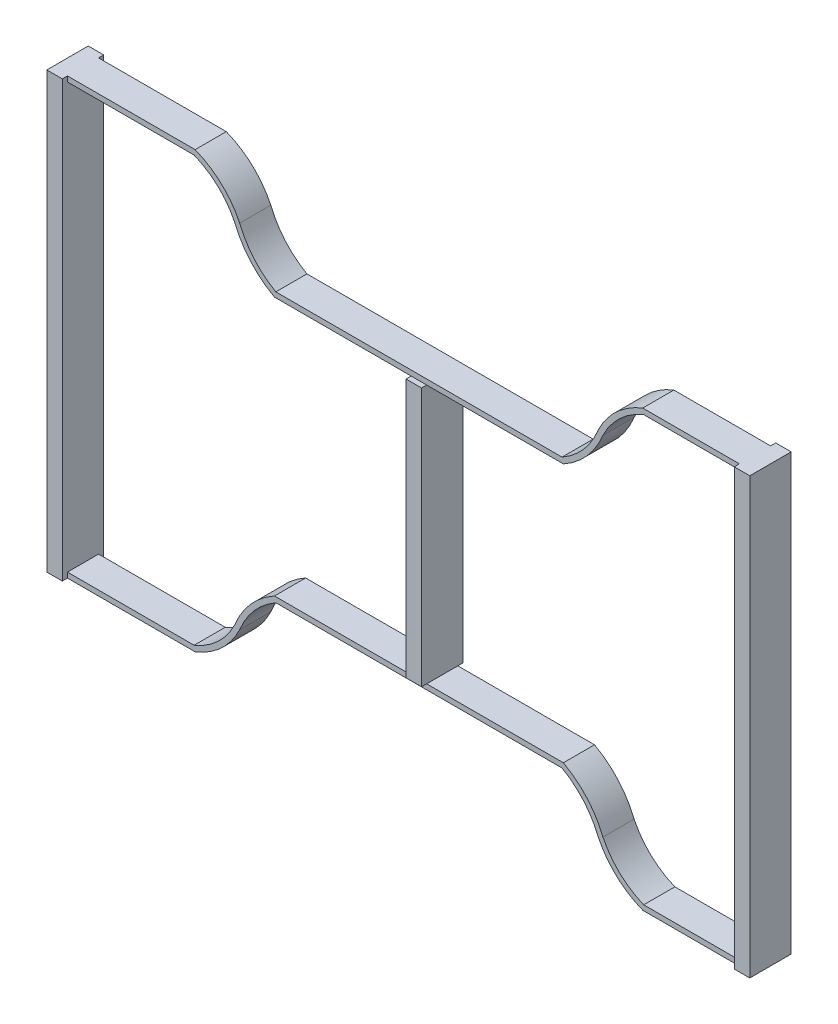
SolidWorks part; units mm, degrees
ref_plane "Front Plane" through (0, 0, 0) normal (0, 0, 1) x (1, 0, 0)
ref_plane "Top Plane" through (0, 0, 0) normal (0, 1, 0) x (1, 0, 0)
ref_plane "Right Plane" through (0, 0, 0) normal (1, 0, 0) x (0, 0, -1)
other "Configuration Table"
sketch "Sketch1" plane through (0, 0, 0) normal (0, 0, 1) x (1, 0, 0)
  line L0 (9.5, 266.7) -> (87.8, 266.7)
  line L1 (0, 0) -> (9.5, 0)
  line L2 (0, 0) -> (0, 266.7)
  line L3 (0, 266.7) -> (9.5, 266.7)
  line L4 (9.5, 0) -> (9.5, 266.7)
  line L5 (137.2756, 215.9) -> (312.7756, 215.9)
  line L6 (362.2513, 266.7) -> (421.5513, 266.7)
  line L7 (9.5, 263.5) -> (87.1857, 263.5)
  line L8 (362.2513, 0) -> (421.5513, 0)
  line L9 (137.2756, 50.8) -> (312.7756, 50.8)
  line L10 (9.5, 0) -> (87.8, 0)
  line L11 (9.5, 0) -> (87.8, 0)
  line L12 (136.4464, 212.7) -> (313.6049, 212.7)
  line L13 (362.8656, 263.5) -> (421.5513, 263.5)
  line L14 (9.5, 266.7) -> (9.5, 263.5)
  line L15 (421.5513, 266.7) -> (421.5513, 263.5)
  line L16 (9.5, 3.2) -> (87.8, 3.2)
  line L17 (136.4464, 54) -> (313.6049, 54)
  line L18 (362.8656, 3.2) -> (421.5513, 3.2)
  line L19 (421.5513, 3.2) -> (421.5513, 0)
  line L20 (9.5, 3.2) -> (9.5, 0)
  line L22 (431.0513, 0) -> (421.5513, 0)
  line L23 (431.0513, 266.7) -> (421.5513, 266.7)
  line L24 (421.5513, 0) -> (421.5513, 266.7)
  line L25 (431.0513, 0) -> (431.0513, 266.7)
  line L26 (229.7756, 212.7) -> (229.7756, 54)
  line L27 (220.2756, 212.7) -> (229.7756, 212.7)
  line L28 (220.2756, 212.7) -> (220.2756, 54)
  line L29 (220.2756, 54) -> (229.7756, 54)
  line L30 (225.0256, 212.7) -> (225.0256, 54)
  arc A0 (87.8, 266.7) -> (115.1137, 241.3) centre (69.2782, 219.3969) cw
  arc A1 (115.1137, 241.3) -> (137.2756, 215.9) centre (162.3044, 260.1063) ccw
  arc A2 (334.9376, 241.3) -> (312.7756, 215.9) centre (287.7469, 260.1063) cw
  arc A3 (362.2513, 266.7) -> (334.9376, 241.3) centre (380.7731, 219.3969) ccw
  arc A4 (362.2513, 0) -> (334.9376, 25.4) centre (380.7731, 47.3031) cw
  arc A5 (334.9376, 25.4) -> (312.7756, 50.8) centre (287.7469, 6.5937) ccw
  arc A6 (87.8, 0) -> (115.1137, 25.4) centre (69.2782, 47.3031) ccw
  arc A7 (115.1137, 25.4) -> (137.2756, 50.8) centre (162.3044, 6.5937) cw
  arc A8 (87.1857, 263.5) -> (112.1818, 240.0133) centre (69.2782, 219.3969) cw
  arc A9 (112.1818, 240.0133) -> (136.4464, 212.7) centre (162.3044, 260.1063) ccw
  arc A10 (337.8694, 240.0133) -> (313.6049, 212.7) centre (287.7469, 260.1063) cw
  arc A11 (362.8656, 263.5) -> (337.8694, 240.0133) centre (380.7731, 219.3969) ccw
  arc A12 (86.6333, 2.9797) -> (112.1818, 26.6867) centre (69.2782, 47.3031) ccw
  arc A13 (112.1818, 26.6867) -> (136.4464, 54) centre (162.3044, 6.5937) cw
  arc A14 (337.8694, 26.6867) -> (313.6049, 54) centre (287.7469, 6.5937) ccw
  arc A15 (362.8656, 3.2) -> (337.8694, 26.6867) centre (380.7731, 47.3031) cw
  dimension "D4" = 25.4
  dimension "D5" = 25.4
  dimension "D1" = 266.7
  dimension "D2" = 9.5
  dimension "D3" = 78.3
  dimension "D6" = 59.3
  dimension "D7" = 3.2
  dimension "D8" = 3.2
  dimension "D9" = 4.75
sketch "Sketch2" plane through (0, 0, 0) normal (0, 0, 1) x (1, 0, 0)
  line L0 (9.5, 266.7) -> (87.8, 266.7)
  line L1 (0, 0) -> (9.5, 0)
  line L2 (0, 0) -> (0, 266.7)
  line L3 (0, 266.7) -> (9.5, 266.7)
  line L4 (9.5, 0) -> (9.5, 266.7)
  line L5 (137.2756, 215.9) -> (312.7756, 215.9)
  line L6 (362.2513, 266.7) -> (421.5513, 266.7)
  line L7 (9.5, 263.5) -> (87.1857, 263.5)
  line L8 (362.2513, 0) -> (421.5513, 0)
  line L9 (137.2756, 50.8) -> (312.7756, 50.8)
  line L10 (9.5, 0) -> (87.8, 0)
  line L11 (9.5, 0) -> (87.8, 0)
  line L12 (136.4464, 212.7) -> (313.6049, 212.7)
  line L13 (362.8656, 263.5) -> (421.5513, 263.5)
  line L14 (9.5, 266.7) -> (9.5, 263.5)
  line L15 (421.5513, 266.7) -> (421.5513, 263.5)
  line L16 (9.5, 3.2) -> (87.8, 3.2)
  line L17 (136.4464, 54) -> (313.6049, 54)
  line L18 (362.8656, 3.2) -> (421.5513, 3.2)
  line L19 (421.5513, 3.2) -> (421.5513, 0)
  line L20 (9.5, 3.2) -> (9.5, 0)
  line L22 (431.0513, 0) -> (421.5513, 0)
  line L23 (431.0513, 266.7) -> (421.5513, 266.7)
  line L24 (421.5513, 0) -> (421.5513, 266.7)
  line L25 (431.0513, 0) -> (431.0513, 266.7)
  line L26 (229.7756, 212.7) -> (229.7756, 54)
  line L27 (220.2756, 212.7) -> (229.7756, 212.7)
  line L28 (220.2756, 212.7) -> (220.2756, 54)
  line L29 (220.2756, 54) -> (229.7756, 54)
  line L30 (225.0256, 212.7) -> (225.0256, 54)
  arc A0 (87.8, 266.7) -> (115.1137, 241.3) centre (69.2782, 219.3969) cw
  arc A1 (115.1137, 241.3) -> (137.2756, 215.9) centre (162.3044, 260.1063) ccw
  arc A2 (334.9376, 241.3) -> (312.7756, 215.9) centre (287.7469, 260.1063) cw
  arc A3 (362.2513, 266.7) -> (334.9376, 241.3) centre (380.7731, 219.3969) ccw
  arc A4 (362.2513, 0) -> (334.9376, 25.4) centre (380.7731, 47.3031) cw
  arc A5 (334.9376, 25.4) -> (312.7756, 50.8) centre (287.7469, 6.5937) ccw
  arc A6 (87.8, 0) -> (115.1137, 25.4) centre (69.2782, 47.3031) ccw
  arc A7 (115.1137, 25.4) -> (137.2756, 50.8) centre (162.3044, 6.5937) cw
  arc A8 (87.1857, 263.5) -> (112.1818, 240.0133) centre (69.2782, 219.3969) cw
  arc A9 (112.1818, 240.0133) -> (136.4464, 212.7) centre (162.3044, 260.1063) ccw
  arc A10 (337.8694, 240.0133) -> (313.6049, 212.7) centre (287.7469, 260.1063) cw
  arc A11 (362.8656, 263.5) -> (337.8694, 240.0133) centre (380.7731, 219.3969) ccw
  arc A12 (86.6333, 2.9797) -> (112.1818, 26.6867) centre (69.2782, 47.3031) ccw
  arc A13 (112.1818, 26.6867) -> (136.4464, 54) centre (162.3044, 6.5937) cw
  arc A14 (337.8694, 26.6867) -> (313.6049, 54) centre (287.7469, 6.5937) ccw
  arc A15 (362.8656, 3.2) -> (337.8694, 26.6867) centre (380.7731, 47.3031) cw
  dimension "D4" = 25.4
  dimension "D5" = 25.4
  dimension "D1" = 266.7
  dimension "D2" = 9.5
  dimension "D3" = 78.3
  dimension "D6" = 59.3
  dimension "D7" = 3.2
  dimension "D8" = 3.2
  dimension "D9" = 4.75
extrude "Boss-Extrude1" add sketch "Sketch1" along normal mid plane 19.1
extrude "Boss-Extrude2" add sketch "Sketch2" along normal mid plane 25.4 contours L1 L4 L3 L2 | L30 L12 L28 L17 | L27 L30 L29 L26 | L24 L22 L25 L23
ref_plane "Plane1" through (0, 0, 0) normal (0.866, 0.5, 0) x (0, 0, -1)
